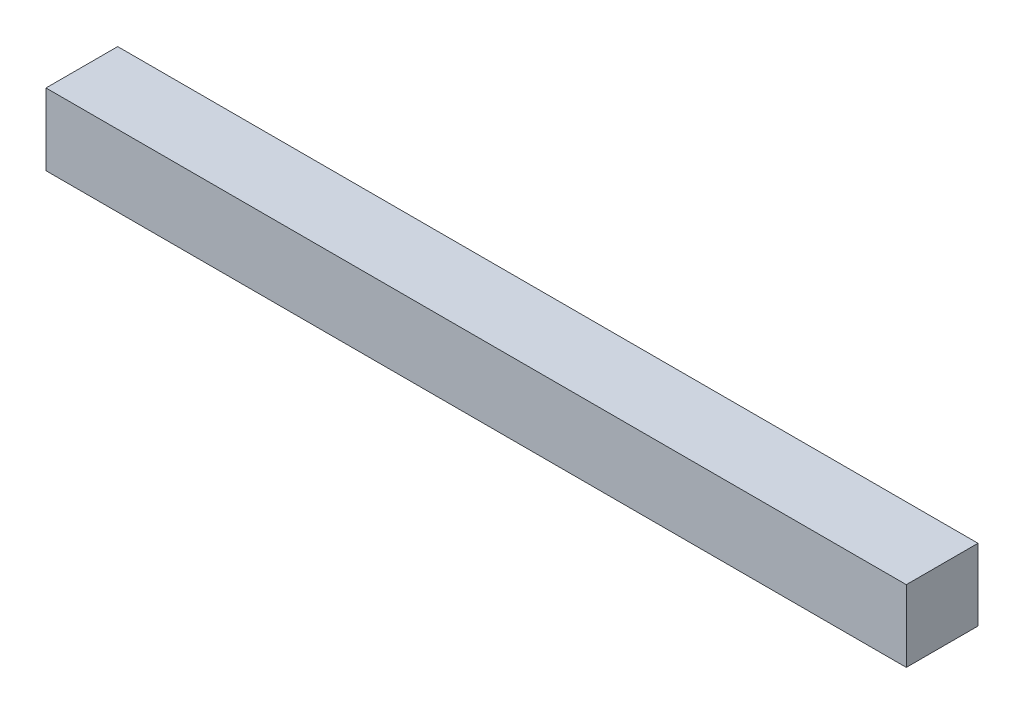
SolidWorks part; units mm, degrees
ref_plane "Front Plane" through (0, 0, 0) normal (0, 0, 1) x (1, 0, 0)
ref_plane "Top Plane" through (0, 0, 0) normal (0, 1, 0) x (1, 0, 0)
ref_plane "Right Plane" through (0, 0, 0) normal (1, 0, 0) x (0, 0, -1)
sketch "Sketch1" plane through (0, 0, 0) normal (0, 1, 0) x (1, 0, 0)
  line L1 (0, 0) -> (228.6, 0)
  line L2 (0, 0) -> (0, 19.05)
  line L3 (0, 19.05) -> (228.6, 19.05)
  line L4 (228.6, 0) -> (228.6, 19.05)
  dimension "D1" = 228.6
  dimension "D2" = 19.05
extrude "Boss-Extrude1" add sketch "Sketch1" along normal blind 19.05
